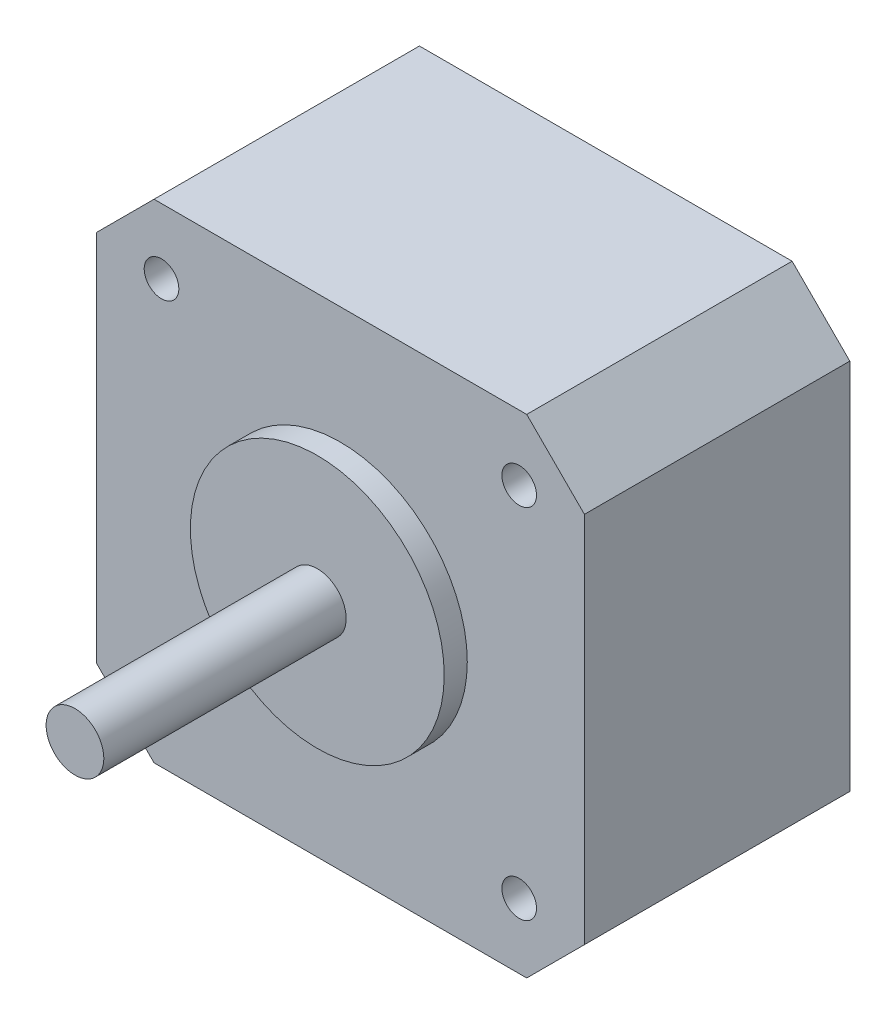
SolidWorks part; units mm, degrees
ref_plane "Front Plane" through (0, 0, 0) normal (0, 0, 1) x (1, 0, 0)
ref_plane "Top Plane" through (0, 0, 0) normal (0, 1, 0) x (1, 0, 0)
ref_plane "Right Plane" through (0, 0, 0) normal (1, 0, 0) x (0, 0, -1)
sketch "Sketch1" plane through (0, 0, 0) normal (0, 0, 1) x (1, 0, 0)
  line L1 (-21.15, 21.15) -> (21.15, 21.15)
  line L2 (-21.15, 21.15) -> (-21.15, -21.15)
  line L3 (-21.15, -21.15) -> (21.15, -21.15)
  line L4 (21.15, 21.15) -> (21.15, -21.15)
  line L5 (-21.15, 21.15) -> (21.15, -21.15) construction
  line L6 (-21.15, -21.15) -> (21.15, 21.15) construction
  point P0 (0, 0)
  dimension "D1" = 42.3
extrude "Boss-Extrude1" add sketch "Sketch1" against normal blind 23
chamfer "Chamfer1" distance 5 angle 45 4 edges at (-21.15, -21.15, -11.5) (21.15, -21.15, -11.5) (21.15, 21.15, -11.5) (-21.15, 21.15, -11.5)
sketch "Sketch3" plane through (0, 0, 0) normal (0, 0, 1) x (1, 0, 0)
  line L0 (0, 0) -> (0, -15.5) construction
  line L1 (0, -15.5) -> (15.5, -15.5) construction
  circle A0 centre (15.5, -15.5) radius 1.5
  circle A1 centre (-15.5, -15.5) radius 1.5
  circle A2 centre (-15.5, 15.5) radius 1.5
  circle A3 centre (15.5, 15.5) radius 1.5
  dimension "D3" = 3
  dimension "D1" = 15.5
  dimension "D2" = 15.5
  dimension "D4" = 4
extrude "Cut-Extrude1" cut sketch "Sketch3" against normal blind 5
sketch "Sketch4" plane through (0, 0, 0) normal (0, 0, 1) x (1, 0, 0)
  circle A0 centre (0, 0) radius 11
  dimension "D1" = 22
extrude "Boss-Extrude2" add sketch "Sketch4" along normal blind 2
sketch "Sketch5" plane through (0, 0, 0) normal (0, 0, 1) x (1, 0, 0)
  circle A0 centre (0, 0) radius 2.5
  dimension "D1" = 5
extrude "Boss-Extrude3" add sketch "Sketch5" along normal blind 23
sketch "Sketch6" plane through (0, 0, -23) normal (0, 0, -1) x (-1, 0, 0)
  line L0 (16.15, -21.15) -> (-16.15, -21.15) construction
  line L1 (-8, -28.15) -> (8, -28.15)
  line L2 (-8, -28.15) -> (-8, -21.15)
  line L3 (-8, -21.15) -> (8, -21.15)
  line L4 (8, -28.15) -> (8, -21.15)
  line L5 (-8, -28.15) -> (8, -21.15) construction
  line L6 (-8, -21.15) -> (8, -28.15) construction
  point P0 (0, -24.65)
  point P5 (0, 0)
  dimension "D1" = 7
  dimension "D2" = 16
extrude "Boss-Extrude4" add sketch "Sketch6" against normal blind 9.6
